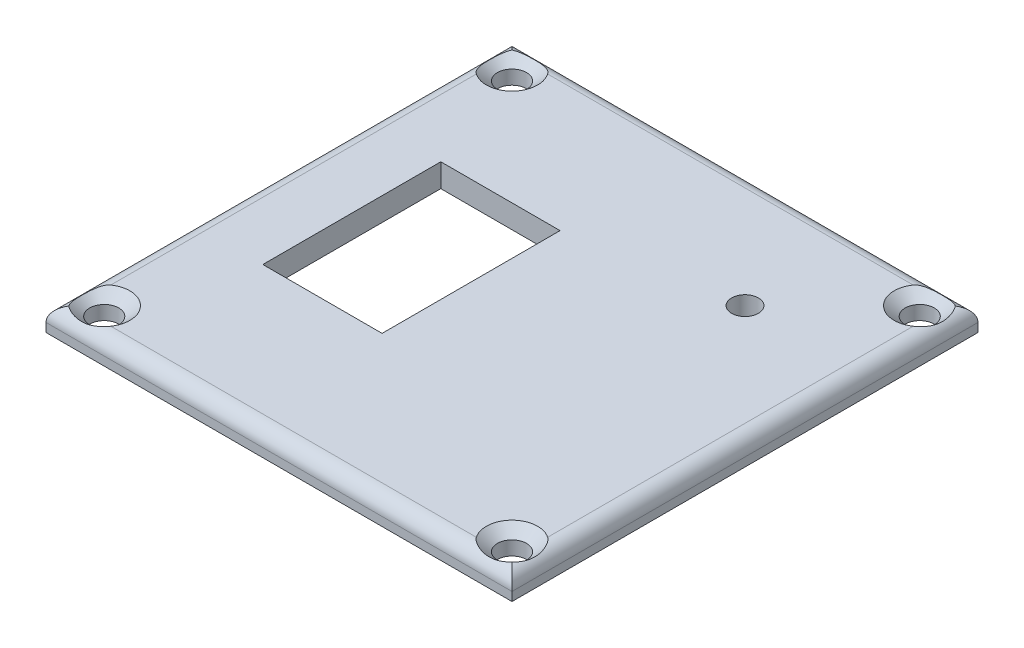
SolidWorks part; units mm, degrees
material "PET"
ref_plane "Front Plane" through (0, 0, 0) normal (0, 0, 1) x (1, 0, 0)
ref_plane "Top Plane" through (0, 0, 0) normal (0, 1, 0) x (1, 0, 0)
ref_plane "Right Plane" through (0, 0, 0) normal (1, 0, 0) x (0, 0, -1)
sketch "Sketch1" plane through (0, 0, 0) normal (0, 1, 0) x (1, 0, 0)
  line L0 (47.625, 3.175) -> (50.8, 3.175) construction
  line L1 (0, 0) -> (50.8, 0)
  line L2 (0, 0) -> (0, 50.8)
  line L3 (0, 50.8) -> (50.8, 50.8)
  line L4 (50.8, 0) -> (50.8, 50.8)
  line L5 (3.175, 3.175) -> (0, 3.175) construction
  line L6 (3.175, 3.175) -> (3.175, 0) construction
  line L7 (3.175, 47.625) -> (3.175, 50.8) construction
  circle A0 centre (3.175, 47.625) radius 2.54 construction
  circle A1 centre (47.625, 47.625) radius 2.54 construction
  circle A2 centre (47.625, 3.175) radius 2.54 construction
  circle A3 centre (3.175, 3.175) radius 2.54 construction
  dimension "D3" = 44.45
  dimension "D5" = 5.08
  dimension "D1" = 50.8
  dimension "D2" = 50.8
  dimension "D4" = 44.45
extrude "Boss-Extrude1" add sketch "Sketch1" along normal blind 2.54
fillet "Fillet1" radius 1.5875 4 edges at (25.4, 2.54, -50.8) (50.8, 2.54, -25.4) (25.4, 2.54, 0) (0, 2.54, -25.4)
hole_wizard "CSK for M3 Flat Head Machine Screw1" positions "Sketch2" profile "Sketch3" countersink size "M3" standard "ANSI Metric" end condition through all
sketch "Sketch2" plane through (0, 2.54, 0) normal (0, 1, 0) x (1, 0, 0)
  point P0 (3.175, 47.625)
  point P3 (47.625, 47.625)
  point P6 (47.625, 3.175)
  point P9 (3.175, 3.175)
sketch "Sketch3" plane through (3.175, 2.54, -47.625) normal (1, 0, 0) x (0, 0, 1)
  line L0 (0, 0) -> (0, 2.54)
  line L1 (0, 2.54) -> (1.5875, 2.54)
  line L2 (1.5875, 2.54) -> (1.5875, 1.0124)
  line L3 (1.5875, 1.0124) -> (2.794, 0)
  line L5 (2.794, 0) -> (0, 0)
  line L6 (-1.5875, 1.0124) -> (-2.794, 0) construction
  line L11 (0, -6.35) -> (0, 107.95) construction
  dimension "Thru Hole Dia." = 3.175
  dimension "Thru Hole Depth" = 2.54
  dimension "Near C'Sink Dia." = 5.588
  dimension "Near C'Sink Angle" = 100
sketch "Sketch4" plane through (0, 2.54, 0) normal (0, 1, 0) x (1, 0, 0)
  line L0 (7.9375, 25.4) -> (1.5875, 25.4)
  line L1 (7.9375, 35.1) -> (20.9375, 35.1)
  line L2 (7.9375, 35.1) -> (7.9375, 15.7)
  line L3 (7.9375, 15.7) -> (20.9375, 15.7)
  line L4 (20.9375, 35.1) -> (20.9375, 15.7)
  line L5 (1.5875, 45.3258) -> (1.5875, 5.4742) construction
  dimension "D1" = 19.4
  dimension "D2" = 13
  dimension "D3" = 6.35
extrude "Cut-Extrude1" cut sketch "Sketch4" against normal through all contours L4 L1 L2 L3
sketch "Sketch5" plane through (0, 2.54, 0) normal (0, 1, 0) x (1, 0, 0)
  line L0 (50.8, 0) -> (50.8, 50.8) construction
  line L1 (0, 50.8) -> (50.8, 50.8) construction
  circle A0 centre (38.1, 38.1) radius 1.4605
  dimension "D1" = 2.921
  dimension "D2" = 12.7
  dimension "D3" = 12.7
extrude "Cut-Extrude2" cut sketch "Sketch5" against normal through all
